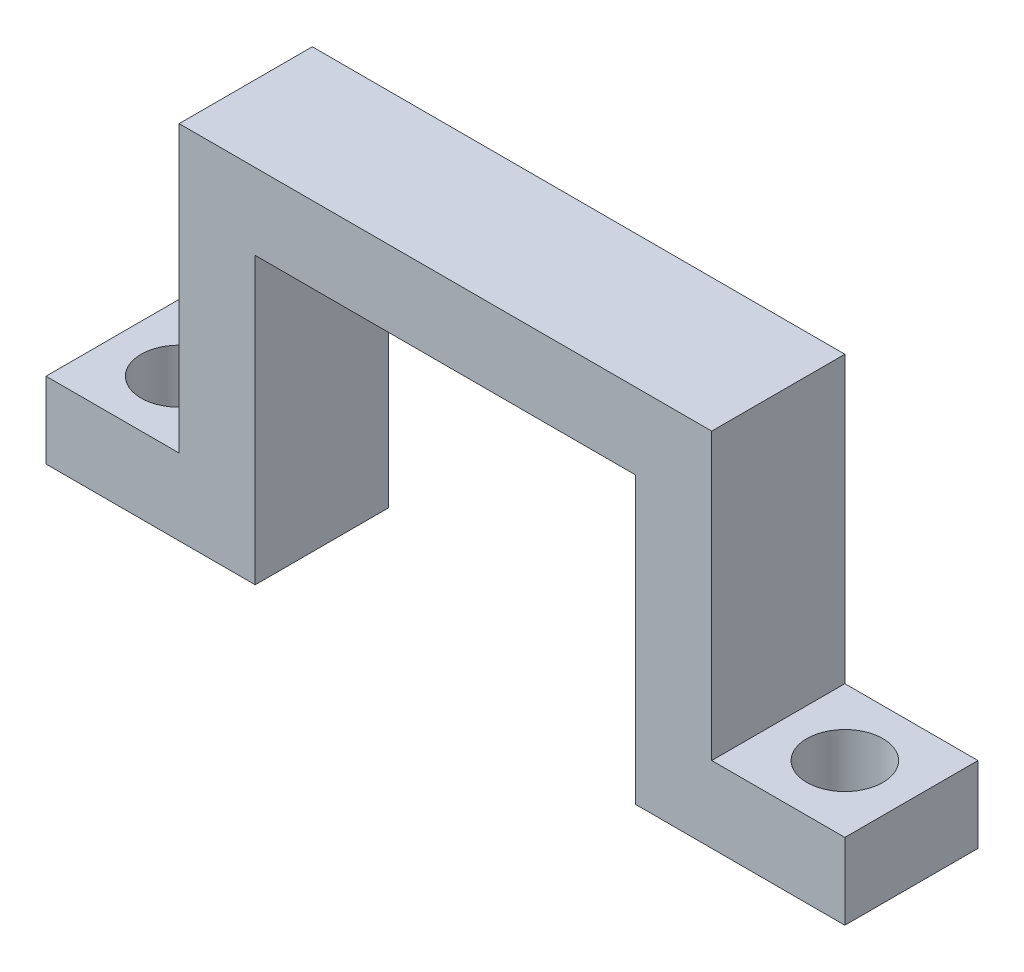
SolidWorks part; units mm, degrees
ref_plane "前视基准面" through (0, 0, 0) normal (0, 0, 1) x (1, 0, 0)
ref_plane "上视基准面" through (0, 0, 0) normal (0, 1, 0) x (1, 0, 0)
ref_plane "右视基准面" through (0, 0, 0) normal (1, 0, 0) x (0, 0, -1)
sketch "草图1" plane through (0, 0, 0) normal (0, 0, 1) x (1, 0, 0)
  line L5 (-2.375, -4) -> (-2.375, 11)
  line L6 (-2.375, 11) -> (17.625, 11)
  line L7 (17.625, -4) -> (17.625, 11)
  line L15 (-6.375, 0) -> (-6.375, 15)
  line L16 (-6.375, 15) -> (21.625, 15)
  line L17 (7.625, 11) -> (7.625, -4) construction
  line L18 (-2.375, -4) -> (-13.375, -4)
  line L19 (-13.375, -4) -> (-13.375, 0)
  line L20 (-13.375, 0) -> (-6.375, 0)
  line L21 (17.625, -4) -> (28.625, -4)
  line L22 (28.625, -4) -> (28.625, 0)
  line L23 (28.625, 0) -> (21.625, 0)
  line L24 (21.625, 0) -> (21.625, 15)
  point P0 (0, 0)
  dimension "D2" = 20
  dimension "D3" = 11
  dimension "D4" = 4
  dimension "D5" = 15
  dimension "D6" = 4
extrude "凸台-拉伸1" add sketch "草图1" along normal blind 7
sketch "草图2" plane through (0, 0, 0) normal (0, 1, 0) x (1, 0, 0)
  line L1 (7.625, 0) -> (7.625, -7) construction
  line L2 (21.625, 0) -> (-6.375, 0) construction
  line L3 (21.625, -7) -> (-6.375, -7) construction
  circle A1 centre (25.125, -3.5) radius 2
  circle A2 centre (-9.875, -3.5) radius 2
  dimension "D1" = 4
extrude "切除-拉伸1" cut sketch "草图2" against normal through all
